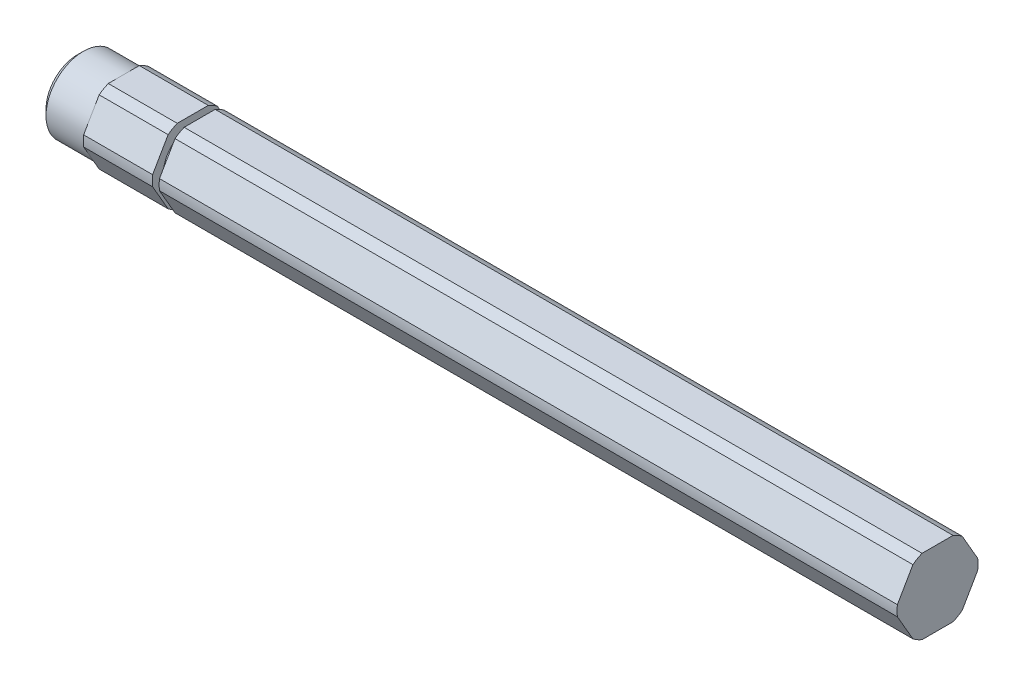
SolidWorks part; units mm, degrees
material "7075-T6 (SN)"
ref_plane "Front Plane" through (0, 0, 0) normal (0, 0, 1) x (1, 0, 0)
ref_plane "Top Plane" through (0, 0, 0) normal (0, 1, 0) x (1, 0, 0)
ref_plane "Right Plane" through (0, 0, 0) normal (1, 0, 0) x (0, 0, -1)
sketch "Sketch1" plane through (0, 0, 0) normal (1, 0, 0) x (0, 0, -1)
  line L1 (2.635, 6.35) -> (-2.635, 6.35)
  line L2 (-4.1818, 5.457) -> (-6.8168, 0.893)
  line L3 (-6.8168, -0.893) -> (-4.1818, -5.457)
  line L4 (-2.635, -6.35) -> (2.635, -6.35)
  line L5 (4.1818, -5.457) -> (6.8168, -0.893)
  line L6 (6.8168, 0.893) -> (4.1818, 5.457)
  circle A0 centre (0, 0) radius 6.35 construction
  arc A1 (-2.635, 6.35) -> (-4.1818, 5.457) centre (0, 0) ccw
  arc A2 (4.1818, 5.457) -> (2.635, 6.35) centre (0, 0) ccw
  arc A3 (6.8168, -0.893) -> (6.8168, 0.893) centre (0, 0) ccw
  arc A4 (2.635, -6.35) -> (4.1818, -5.457) centre (0, 0) ccw
  arc A5 (-4.1818, -5.457) -> (-2.635, -6.35) centre (0, 0) ccw
  arc A6 (-6.8168, 0.893) -> (-6.8168, -0.893) centre (0, 0) ccw
  dimension "D2" = 13.75
  dimension "D1" = 12.7
extrude "Boss-Extrude1" add sketch "Sketch1" along normal mid plane 146.05
sketch "Sketch2" plane through (-73.025, 0, 0) normal (-1, 0, 0) x (0, 0, 1)
  line L6 (-4.1818, 5.457) -> (-6.8168, 0.893)
  line L7 (-6.8168, -0.893) -> (-4.1818, -5.457)
  line L8 (-2.635, -6.35) -> (2.635, -6.35)
  line L9 (4.1818, -5.457) -> (6.8168, -0.893)
  line L10 (6.8168, 0.893) -> (4.1818, 5.457)
  line L11 (2.635, 6.35) -> (-2.635, 6.35)
  line L12 (-4.1818, 5.457) -> (-6.8168, 0.893)
  line L13 (-6.8168, -0.893) -> (-4.1818, -5.457)
  line L14 (-2.635, -6.35) -> (2.635, -6.35)
  line L15 (4.1818, -5.457) -> (6.8168, -0.893)
  line L16 (6.8168, 0.893) -> (4.1818, 5.457)
  line L17 (2.635, 6.35) -> (-2.635, 6.35)
  circle A0 centre (0, 0) radius 6.3373
  arc A7 (-2.635, 6.35) -> (-4.1818, 5.457) centre (0, 0) ccw
  arc A8 (-6.8168, 0.893) -> (-6.8168, -0.893) centre (0, 0) ccw
  arc A9 (-4.1818, -5.457) -> (-2.635, -6.35) centre (0, 0) ccw
  arc A10 (2.635, -6.35) -> (4.1818, -5.457) centre (0, 0) ccw
  arc A11 (6.8168, -0.893) -> (6.8168, 0.893) centre (0, 0) ccw
  arc A12 (4.1818, 5.457) -> (2.635, 6.35) centre (0, 0) ccw
  arc A13 (-2.635, 6.35) -> (-4.1818, 5.457) centre (0, 0) ccw
  arc A14 (-6.8168, 0.893) -> (-6.8168, -0.893) centre (0, 0) ccw
  arc A15 (-4.1818, -5.457) -> (-2.635, -6.35) centre (0, 0) ccw
  arc A16 (2.635, -6.35) -> (4.1818, -5.457) centre (0, 0) ccw
  arc A17 (6.8168, -0.893) -> (6.8168, 0.893) centre (0, 0) ccw
  arc A18 (4.1818, 5.457) -> (2.635, 6.35) centre (0, 0) ccw
  dimension "D1" = 12.6746
  dimension "D2" = 0
extrude "Cut-Extrude1" cut sketch "Sketch2" against normal blind 7.8867
ref_plane "Plane1" through (-53.4289, 0, 0) normal (-1, 0, 0) x (0, 0, 1)
sketch "Sketch3" plane through (-53.4289, 0, 0) normal (-1, 0, 0) x (0, 0, 1)
  line L6 (-4.1818, 5.457) -> (-6.8168, 0.893)
  line L7 (-6.8168, -0.893) -> (-4.1818, -5.457)
  line L8 (-2.635, -6.35) -> (2.635, -6.35)
  line L9 (4.1818, -5.457) -> (6.8168, -0.893)
  line L10 (6.8168, 0.893) -> (4.1818, 5.457)
  line L11 (2.635, 6.35) -> (-2.635, 6.35)
  line L12 (-4.1818, 5.457) -> (-6.8168, 0.893)
  line L13 (-6.8168, -0.893) -> (-4.1818, -5.457)
  line L14 (-2.635, -6.35) -> (2.635, -6.35)
  line L15 (4.1818, -5.457) -> (6.8168, -0.893)
  line L16 (6.8168, 0.893) -> (4.1818, 5.457)
  line L17 (2.635, 6.35) -> (-2.635, 6.35)
  circle A0 centre (0, 0) radius 5.0292
  arc A7 (-2.635, 6.35) -> (-4.1818, 5.457) centre (0, 0) ccw
  arc A8 (-6.8168, 0.893) -> (-6.8168, -0.893) centre (0, 0) ccw
  arc A9 (-4.1818, -5.457) -> (-2.635, -6.35) centre (0, 0) ccw
  arc A10 (2.635, -6.35) -> (4.1818, -5.457) centre (0, 0) ccw
  arc A11 (6.8168, -0.893) -> (6.8168, 0.893) centre (0, 0) ccw
  arc A12 (4.1818, 5.457) -> (2.635, 6.35) centre (0, 0) ccw
  arc A13 (-2.635, 6.35) -> (-4.1818, 5.457) centre (0, 0) ccw
  arc A14 (-6.8168, 0.893) -> (-6.8168, -0.893) centre (0, 0) ccw
  arc A15 (-4.1818, -5.457) -> (-2.635, -6.35) centre (0, 0) ccw
  arc A16 (2.635, -6.35) -> (4.1818, -5.457) centre (0, 0) ccw
  arc A17 (6.8168, -0.893) -> (6.8168, 0.893) centre (0, 0) ccw
  arc A18 (4.1818, 5.457) -> (2.635, 6.35) centre (0, 0) ccw
  dimension "D1" = 10.0584
  dimension "D2" = 0
extrude "Cut-Extrude2" cut sketch "Sketch3" against normal blind 1.1684
sketch "Sketch4" plane through (-73.025, 0, 0) normal (-1, 0, 0) x (0, 0, 1)
  circle A0 centre (0, 0) radius 3.175
  dimension "D1" = 6.35
extrude "Cut-Extrude3" cut sketch "Sketch4" against normal blind 9.0246
sketch "Sketch6" plane through (0, 0, 0) normal (0, 0, 1) x (1, 0, 0)
  line L0 (-62.0954, 0) -> (-64.0004, 0)
  line L1 (-64.0004, 0) -> (-64.0004, 3.175)
  line L2 (-64.0004, 3.175) -> (-62.0954, 0)
  line L3 (-64.0004, 3.175) -> (-64.0004, -3.175) construction
  line L5 (-64.0004, 3.175) -> (-73.025, 3.175) construction
  dimension "D1" = 1.905
revolve "Cut-Revolve1" cut sketch "Sketch6" angle 360 about L0
chamfer "Chamfer1" distance 1.016 angle 45 1 edges at (-73.025, 0, 6.3373)
